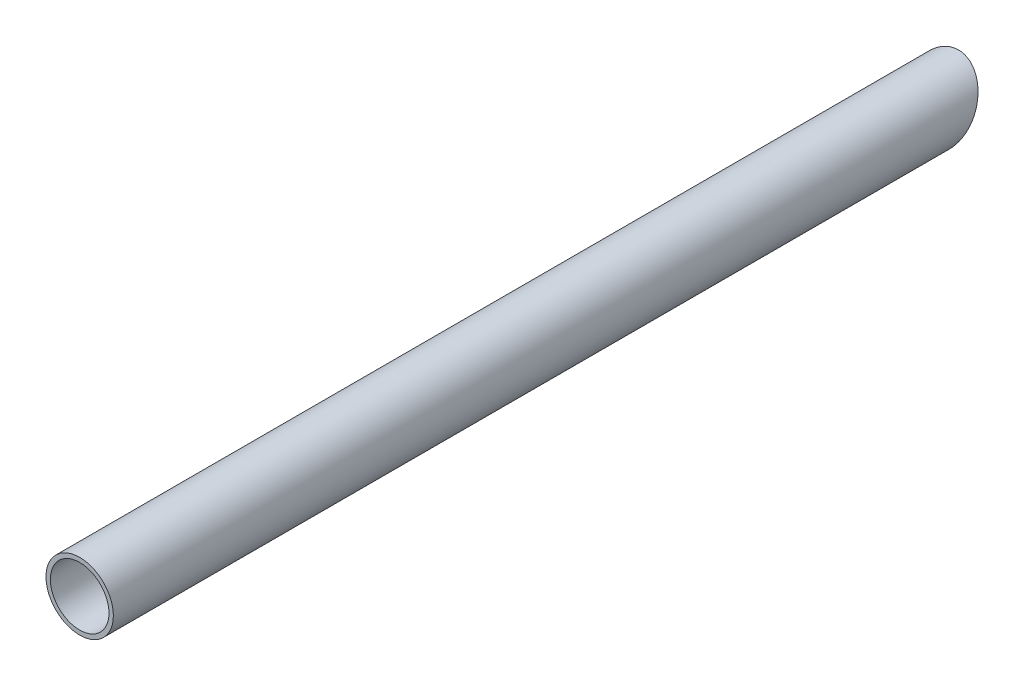
SolidWorks part; units mm, degrees
ref_plane "Front Plane" through (0, 0, 0) normal (0, 0, 1) x (1, 0, 0)
ref_plane "Top Plane" through (0, 0, 0) normal (0, 1, 0) x (1, 0, 0)
ref_plane "Right Plane" through (0, 0, 0) normal (1, 0, 0) x (0, 0, -1)
sketch "Sketch1" plane through (0, 0, 0) normal (0, 0, 1) x (1, 0, 0)
  circle A0 centre (0, 0) radius 11.5
  dimension "D1" = 23
extrude "Extrude-Thin1" add sketch "Sketch1" along normal mid plane 300 thin thin type one direction reverse wall 1.5
sketch "Sketch2" plane through (0, 0, 0) normal (1, 0, 0) x (0, 0, -1)
  line L0 (150, 11.5) -> (136.7209, -11.5)
  line L1 (-150, -11.5) -> (150, -11.5) construction
  line L2 (150, -11.5) -> (150, 11.5) construction
  line L3 (136.7209, -11.5) -> (150, -11.5)
  line L4 (150, -11.5) -> (150, 11.5)
  point P2 (146.4565, -7.5428)
  point P3 (150, 7.5328)
  point P6 (0, 0)
  point P9 (0, 0)
  point P10 (0, 0)
  dimension "D1" = 60
extrude "Cut-Extrude1" cut sketch "Sketch2" against normal mid plane 30
